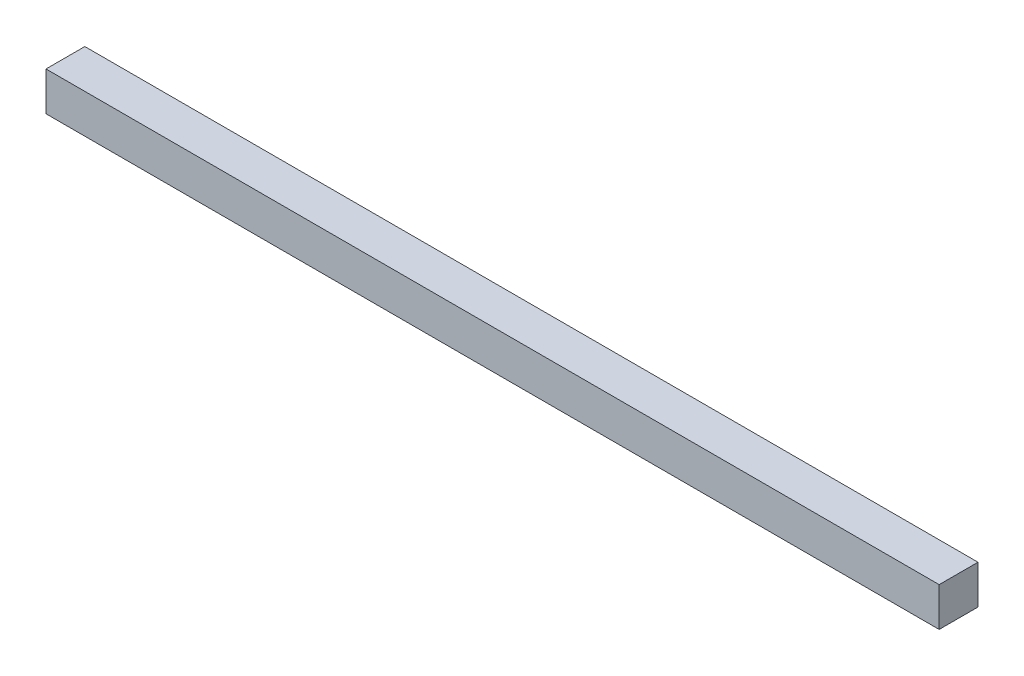
SolidWorks part; units mm, degrees
material "AISI 1035 Сталь (SS)"
ref_plane "Спереди" through (0, 0, 0) normal (0, 0, 1) x (1, 0, 0)
ref_plane "Сверху" through (0, 0, 0) normal (0, 1, 0) x (1, 0, 0)
ref_plane "Справа" through (0, 0, 0) normal (1, 0, 0) x (0, 0, -1)
sketch "Эскиз1" plane through (0, 0, 0) normal (0, 0, 1) x (1, 0, 0)
  line L1 (44.0503, 37.6311) -> (734.0503, 37.6311)
  line L2 (44.0503, 37.6311) -> (44.0503, 7.6311)
  line L3 (44.0503, 7.6311) -> (734.0503, 7.6311)
  line L4 (734.0503, 37.6311) -> (734.0503, 7.6311)
  dimension "D1" = 690
  dimension "D2" = 30
extrude "Бобышка-Вытянуть1" add sketch "Эскиз1" along normal blind 30
